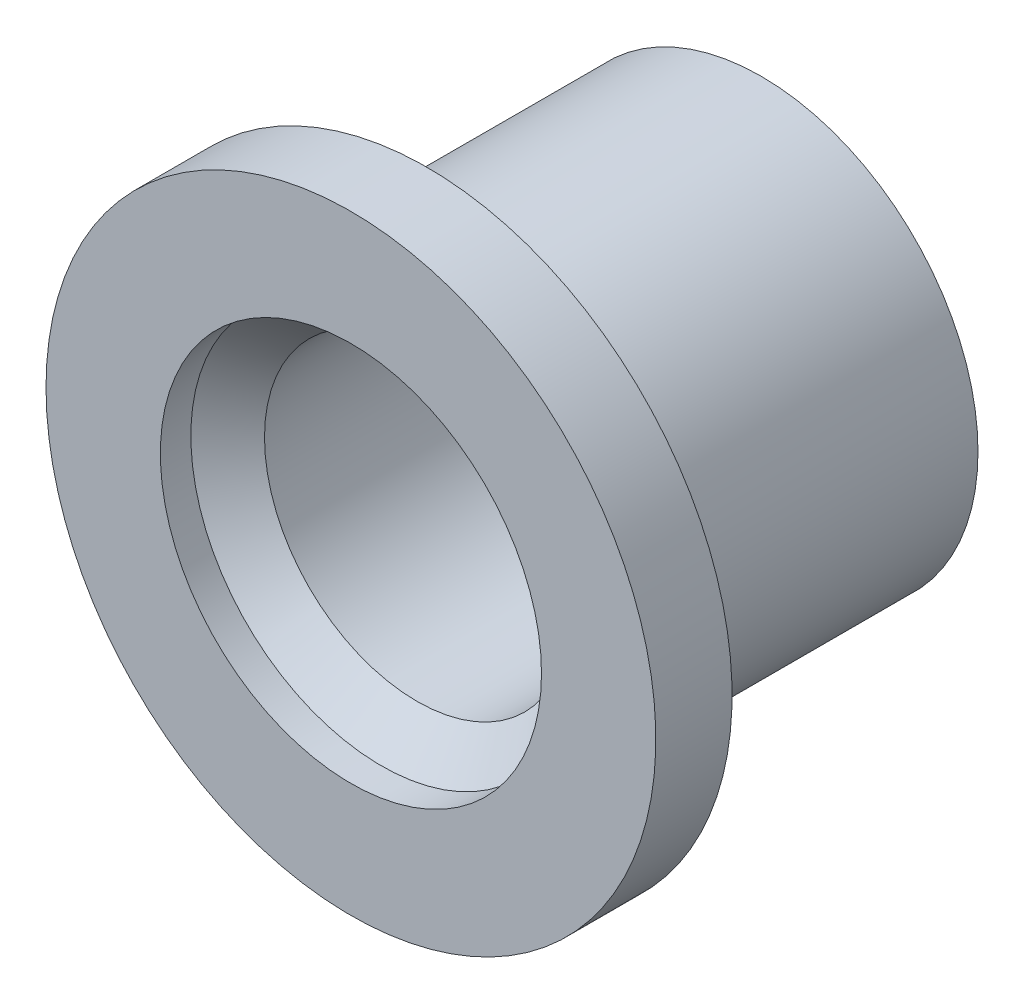
SolidWorks part; units mm, degrees
ref_plane "Front Plane" through (0, 0, 0) normal (0, 0, 1) x (1, 0, 0)
ref_plane "Top Plane" through (0, 0, 0) normal (0, 1, 0) x (1, 0, 0)
ref_plane "Right Plane" through (0, 0, 0) normal (1, 0, 0) x (0, 0, -1)
sketch "Sketch1" plane through (0, 0, 0) normal (0, 0, 1) x (1, 0, 0)
  circle A0 centre (0, 0) radius 5.08
  circle A1 centre (0, 0) radius 2.54
  dimension "D1" = 5.08
  dimension "D2" = 10.16
extrude "Boss-Extrude1" add sketch "Sketch1" along normal blind 0.762
chamfer "Chamfer2" distance 0.635 angle 43 1 edges at (2.54, 0, 0.762)
sketch "Sketch3" plane through (0, 0, 0.762) normal (0, 0, 1) x (1, 0, 0)
  circle A0 centre (0, 0) radius 3.175
  circle A1 centre (0, 0) radius 5.08
  dimension "D1" = 6.35
extrude "Boss-Extrude3" add sketch "Sketch3" along normal blind 0.508
sketch "Sketch4" plane through (0, 0, 0) normal (0, 0, -1) x (-1, 0, 0)
  circle A0 centre (0, 0) radius 2.54
  circle A1 centre (0, 0) radius 3.6094
extrude "Boss-Extrude4" add sketch "Sketch4" along normal offset from surface (5.5677 mm away) 0.0254
sketch "Sketch5" plane through (0, 0, 0) normal (1, 0, 0) x (0, 0, -1)
